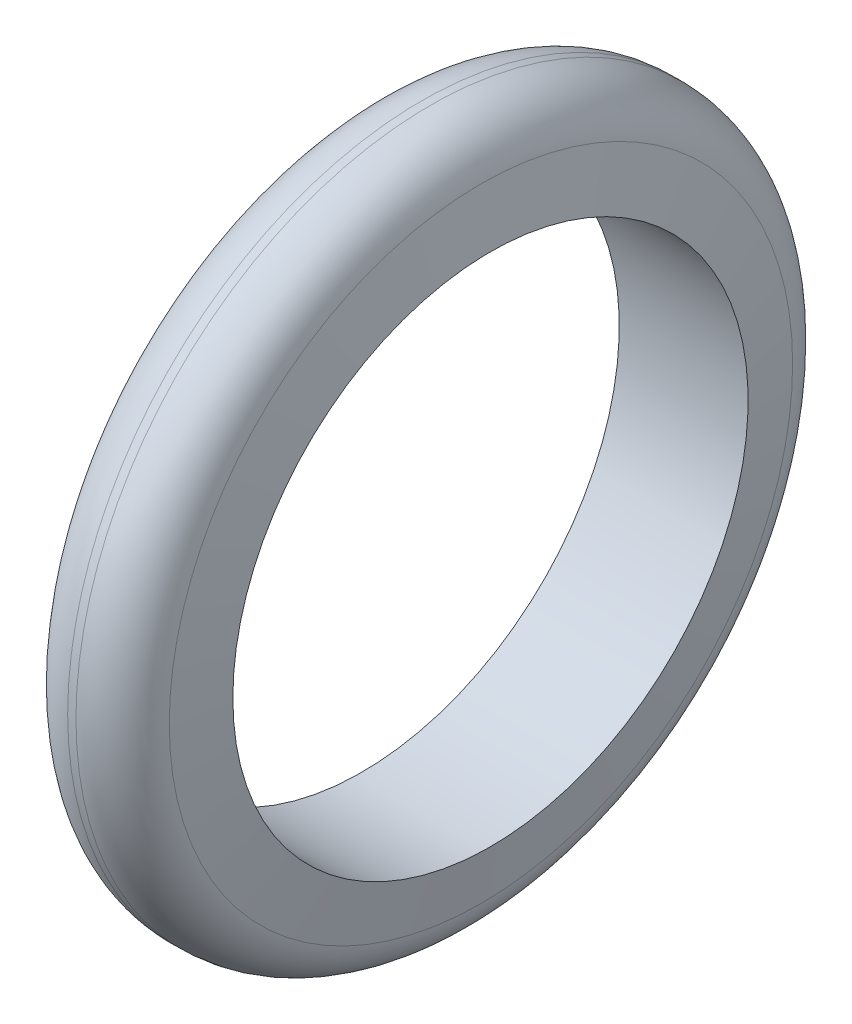
SolidWorks part; units mm, degrees
ref_plane "Front Plane" through (0, 0, 0) normal (0, 0, 1) x (1, 0, 0)
ref_plane "Top Plane" through (0, 0, 0) normal (0, 1, 0) x (1, 0, 0)
ref_plane "Right Plane" through (0, 0, 0) normal (1, 0, 0) x (0, 0, -1)
sketch "Sketch1" plane through (0, 0, 0) normal (0, 0, 1) x (1, 0, 0)
  line L0 (0, 0) -> (153.2089, 0) construction
  line L1 (0, 0) -> (0, 91.4465) construction
  line L2 (-7.3551, 55) -> (7.3551, 55)
  line L3 (7.3551, 55) -> (10, 40)
  line L4 (10, 40) -> (-10, 40)
  line L5 (-10, 40) -> (-7.3551, 55)
  dimension "D1" = 80
  dimension "D2" = 110
  dimension "D3" = 20
  dimension "D4" = 10
revolve "Revolve1" add sketch "Sketch1" angle 360 about L0
fillet "Fillet1" radius 8 1 edges at (7.3551, 0, 55)
fillet "Fillet2" radius 8 1 edges at (-7.3551, 0, 55)
